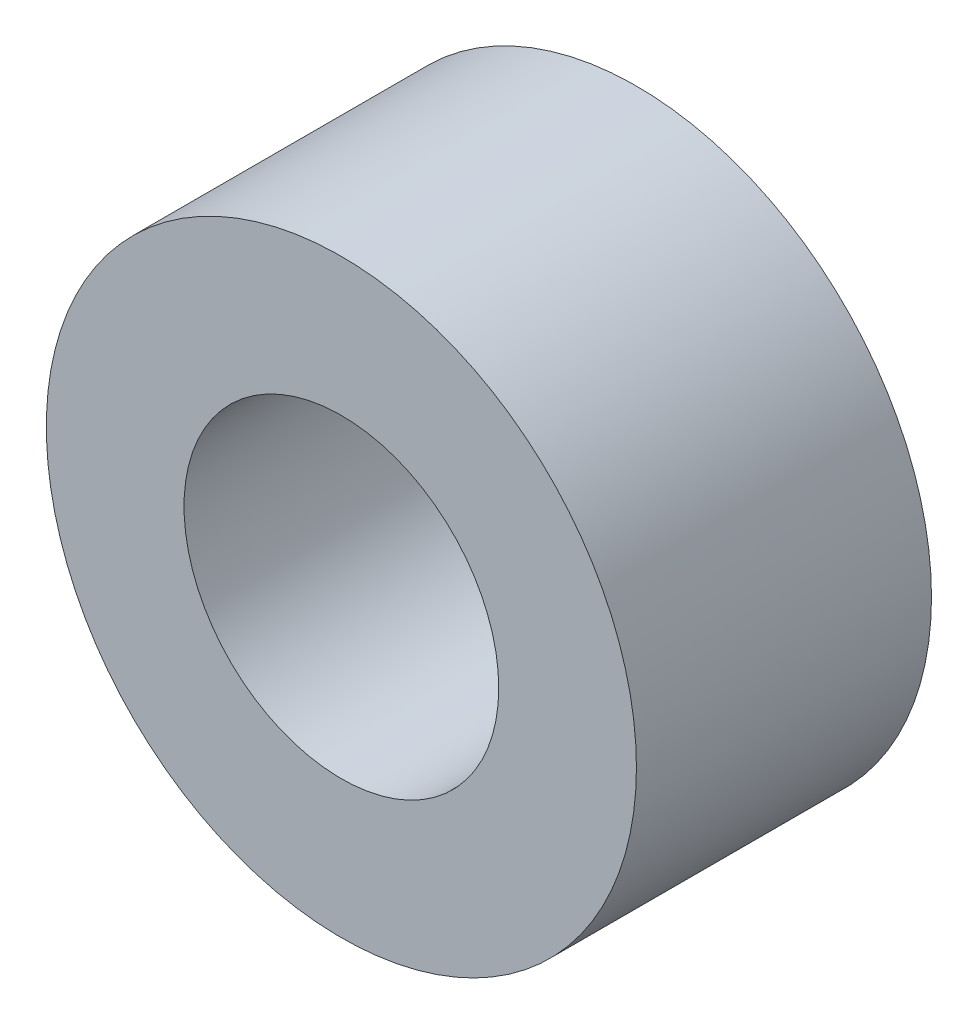
SolidWorks part; units mm, degrees
ref_plane "前视基准面" through (0, 0, 0) normal (0, 0, 1) x (1, 0, 0)
ref_plane "上视基准面" through (0, 0, 0) normal (0, 1, 0) x (1, 0, 0)
ref_plane "右视基准面" through (0, 0, 0) normal (1, 0, 0) x (0, 0, -1)
other "Configuration Table"
sketch "草图1" plane through (0, 0, 0) normal (0, 0, 1) x (1, 0, 0)
  circle A0 centre (0, 0) radius 3
  circle A1 centre (0, 0) radius 1.6
extrude "隔套_内径3p2外径6" add sketch "草图1" along normal blind 3
